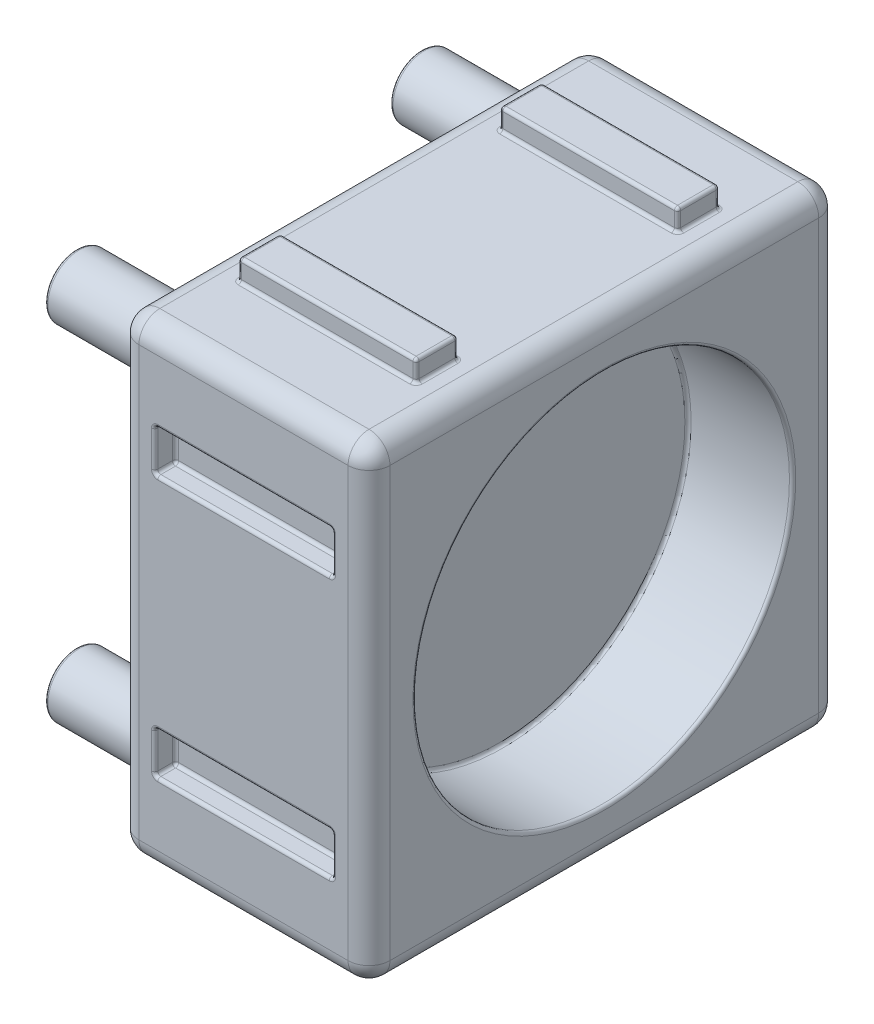
SolidWorks part; units mm, degrees
ref_plane "Front Plane" through (0, 0, 0) normal (0, 0, 1) x (1, 0, 0)
ref_plane "Top Plane" through (0, 0, 0) normal (0, 1, 0) x (1, 0, 0)
ref_plane "Right Plane" through (0, 0, 0) normal (1, 0, 0) x (0, 0, -1)
sketch "Sketch1" plane through (0, 0, 0) normal (0, 1, 0) x (1, 0, 0)
  line L1 (-6, 11.25) -> (6, 11.25)
  line L2 (-6, 11.25) -> (-6, -11.25)
  line L3 (-6, -11.25) -> (6, -11.25)
  line L4 (6, 11.25) -> (6, -11.25)
  line L5 (-6, 11.25) -> (6, -11.25) construction
  line L6 (-6, -11.25) -> (6, 11.25) construction
  point P0 (0, 0)
  dimension "D1" = 22.5
  dimension "D2" = 12
extrude "Boss-Extrude1" add sketch "Sketch1" along normal blind 22.5
sketch "Sketch2" plane through (6, 0, 0) normal (1, 0, 0) x (0, 0, -1)
  line L0 (0, 22.5) -> (0, 0) construction
  line L1 (-11.25, 22.5) -> (11.25, 22.5) construction
  line L2 (-11.25, 0) -> (11.25, 0) construction
  line L3 (-11.25, 11.25) -> (11.25, 11.25) construction
  line L4 (-11.25, 22.5) -> (-11.25, 0) construction
  line L5 (11.25, 22.5) -> (11.25, 0) construction
  circle A0 centre (0, 11.25) radius 9
  dimension "D1" = 18
extrude "Cut-Extrude1" cut sketch "Sketch2" against normal blind 5
sketch "Sketch3" plane through (-6, 0, 0) normal (-1, 0, 0) x (0, 0, 1)
  line L0 (-11.25, 22.5) -> (11.25, 22.5) construction
  line L1 (11.25, 22.5) -> (11.25, 0) construction
  line L2 (0, 0) -> (0, 22.5) construction
  line L3 (-11.25, 0) -> (11.25, 0) construction
  line L4 (11.25, 11.25) -> (-11.25, 11.25) construction
  line L5 (-11.25, 22.5) -> (-11.25, 0) construction
  circle A0 centre (8.25, 19.5) radius 1.5
  circle A1 centre (8.25, 3) radius 1.5
  circle A2 centre (-8.25, 19.5) radius 1.5
  circle A3 centre (-8.25, 3) radius 1.5
  dimension "D1" = 3
  dimension "D2" = 3
  dimension "D3" = 3
extrude "Boss-Extrude2" add sketch "Sketch3" along normal blind 5
sketch "Sketch4" plane through (-6, 0, 0) normal (-1, 0, 0) x (0, 0, 1)
  line L0 (11.25, 11.25) -> (-11.25, 11.25) construction
  line L1 (11.25, 22.5) -> (11.25, 0) construction
  line L2 (-11.25, 22.5) -> (-11.25, 0) construction
  line L3 (0, 0) -> (0, 22.5) construction
  line L4 (-11.25, 0) -> (11.25, 0) construction
  line L5 (-11.25, 22.5) -> (11.25, 22.5) construction
  circle A0 centre (0, 11.25) radius 1.5
  dimension "D1" = 3
extrude "Boss-Extrude3" add sketch "Sketch4" along normal blind 3
fillet "Fillet3" radius 1 12 edges at (-6, 11.25, -11.25) (0, 22.5, -11.25) (0, 0, -11.25) (-6, 0, 0) (0, 22.5, 11.25) (-6, 22.5, 0) (-6, 11.25, 11.25) (0, 0, 11.25) (6, 11.25, 11.25) (6, 0, 0) (6, 11.25, -11.25) (6, 22.5, 0)
sketch "Sketch5" plane through (0, 0, 0) normal (0, -1, 0) x (-1, 0, 0)
  line L0 (5, 10.25) -> (-5, 10.25) construction
  line L1 (4.25, 7.25) -> (-4.25, 7.25)
  line L2 (4.25, 7.25) -> (4.25, 5.25)
  line L3 (4.25, 5.25) -> (-4.25, 5.25)
  line L4 (-4.25, 7.25) -> (-4.25, 5.25)
  line L5 (-6, -10.25) -> (-6, 10.25) construction
  line L7 (-6, 0) -> (5, 0) construction
  line L8 (5, -10.25) -> (5, 10.25) construction
  line L9 (4.25, -7.25) -> (4.25, -5.25)
  line L10 (-4.25, -7.25) -> (-4.25, -5.25)
  line L11 (4.25, -7.25) -> (-4.25, -7.25)
  line L12 (4.25, -5.25) -> (-4.25, -5.25)
  dimension "D1" = 3
  dimension "D2" = 0.75
  dimension "D3" = 2
  dimension "D4" = 8.5
extrude "Cut-Extrude2" cut sketch "Sketch5" against normal blind 1
sketch "Sketch6" plane through (0, 0, 11.25) normal (0, 0, 1) x (1, 0, 0)
  line L0 (-5, 1) -> (5, 1) construction
  line L1 (-4.25, 4) -> (4.25, 4)
  line L2 (-4.25, 4) -> (-4.25, 6)
  line L3 (-4.25, 6) -> (4.25, 6)
  line L4 (4.25, 4) -> (4.25, 6)
  line L5 (5, 1) -> (5, 21.5) construction
  line L6 (5, 11.25) -> (-5, 11.25) construction
  line L7 (-5, 21.5) -> (-5, 1) construction
  line L8 (-4.25, 18.5) -> (-4.25, 16.5)
  line L9 (4.25, 18.5) -> (4.25, 16.5)
  line L10 (-4.25, 18.5) -> (4.25, 18.5)
  line L11 (-4.25, 16.5) -> (4.25, 16.5)
  dimension "D1" = 3
  dimension "D2" = 0.75
  dimension "D3" = 8.5
  dimension "D4" = 2
extrude "Cut-Extrude3" cut sketch "Sketch6" against normal blind 1
sketch "Sketch7" plane through (0, 22.5, 0) normal (0, 1, 0) x (1, 0, 0)
  line L0 (-5, -10.25) -> (5, -10.25) construction
  line L1 (-4.25, -7.25) -> (4.25, -7.25)
  line L2 (-4.25, -7.25) -> (-4.25, -5.25)
  line L3 (-4.25, -5.25) -> (4.25, -5.25)
  line L4 (4.25, -7.25) -> (4.25, -5.25)
  line L5 (5, -10.25) -> (5, 10.25) construction
  line L6 (-5, 0) -> (5, 0) construction
  line L7 (-5, 10.25) -> (-5, -10.25) construction
  line L8 (4.25, 7.25) -> (4.25, 5.25)
  line L9 (-4.25, 7.25) -> (-4.25, 5.25)
  line L10 (-4.25, 7.25) -> (4.25, 7.25)
  line L11 (-4.25, 5.25) -> (4.25, 5.25)
  dimension "D1" = 3
  dimension "D2" = 0.75
  dimension "D3" = 8.5
  dimension "D4" = 2
extrude "Boss-Extrude4" add sketch "Sketch7" along normal blind 1
sketch "Sketch8" plane through (0, 0, -11.25) normal (0, 0, -1) x (-1, 0, 0)
  line L0 (5, 21.5) -> (-5, 21.5) construction
  line L1 (4.25, 18.5) -> (-4.25, 18.5)
  line L2 (4.25, 18.5) -> (4.25, 16.5)
  line L3 (4.25, 16.5) -> (-4.25, 16.5)
  line L4 (-4.25, 18.5) -> (-4.25, 16.5)
  line L5 (-5, 21.5) -> (-5, 1) construction
  line L6 (5, 11.25) -> (-5, 11.25) construction
  line L7 (5, 1) -> (5, 21.5) construction
  line L8 (-4.25, 4) -> (-4.25, 6)
  line L9 (4.25, 4) -> (-4.25, 4)
  line L10 (4.25, 4) -> (4.25, 6)
  line L11 (4.25, 6) -> (-4.25, 6)
  dimension "D1" = 3
  dimension "D2" = 0.75
  dimension "D3" = 8.5
  dimension "D4" = 2
extrude "Boss-Extrude5" add sketch "Sketch8" along normal blind 1
fillet "Fillet4" radius 0.15 96 edges at (-4.25, 17.5, 10.25) (-4.25, 17.5, 11.25) (0, 18.5, 10.25) (-4.25, 18.5, 10.75) (0, 18.5, 11.25) (4.25, 17.5, 10.25) (4.25, 18.5, 10.75) (4.25, 17.5, 11.25) (-4.25, 16.5, 10.75) (0, 16.5, 10.25) (4.25, 16.5, 10.75) (0, 16.5, 11.25) (0, 4, 10.25) (0, 4, 11.25) (4.25, 4, 10.75) (4.25, 5, 10.25) (4.25, 5, 11.25) (4.25, 6, 10.75) (0, 6, 10.25) (0, 6, 11.25) (-4.25, 6, 10.75) (-4.25, 5, 10.25) (-4.25, 4, 10.75) (-4.25, 5, 11.25) (4.25, 1, 6.25) (4.25, 0, 6.25) (4.25, 0.5, 7.25) (0, 1, 7.25) (0, 0, 7.25) (0, 1, 5.25) (4.25, 0.5, 5.25) (0, 0, 5.25) (-4.25, 0.5, 7.25) (-4.25, 1, 6.25) (-4.25, 0.5, 5.25) (-4.25, 0, 6.25) (-4.25, 1, -6.25) (-4.25, 0, -6.25) (-4.25, 0.5, -7.25) (0, 1, -7.25) (0, 0, -7.25) (4.25, 0.5, -7.25) (4.25, 1, -6.25) (4.25, 0, -6.25) (4.25, 0.5, -5.25) (0, 1, -5.25) (-4.25, 0.5, -5.25) (0, 0, -5.25) (-4.25, 5, -12.25) (-4.25, 5, -11.25) (-4.25, 6, -11.75) (0, 6, -12.25) (0, 6, -11.25) (0, 4, -12.25) (-4.25, 4, -11.75) (0, 4, -11.25) (4.25, 6, -11.75) (4.25, 5, -12.25) (4.25, 4, -11.75) (4.25, 5, -11.25) (4.25, 17.5, -12.25) (4.25, 17.5, -11.25) (4.25, 16.5, -11.75) (0, 16.5, -12.25) (0, 16.5, -11.25) (-4.25, 16.5, -11.75) (-4.25, 17.5, -12.25) (-4.25, 17.5, -11.25) (-4.25, 18.5, -11.75) (0, 18.5, -12.25) (4.25, 18.5, -11.75) (0, 18.5, -11.25) (-4.25, 23.5, -6.25) (-4.25, 22.5, -6.25) (-4.25, 23, -5.25) (0, 23.5, -5.25) (0, 22.5, -5.25) (0, 23.5, -7.25) (-4.25, 23, -7.25) (0, 22.5, -7.25) (4.25, 23, -5.25) (4.25, 23.5, -6.25) (4.25, 23, -7.25) (4.25, 22.5, -6.25) (0, 23.5, 5.25) (0, 22.5, 5.25) (4.25, 23.5, 6.25) (4.25, 23, 5.25) (4.25, 22.5, 6.25) (0, 23.5, 7.25) (4.25, 23, 7.25) (0, 22.5, 7.25) (-4.25, 23, 5.25) (-4.25, 23.5, 6.25) (-4.25, 23, 7.25) (-4.25, 22.5, 6.25)
fillet "Fillet5" radius 0.15 10 edges at (-6, 3, 6.75) (-11, 3, 6.75) (-6, 19.5, 6.75) (-11, 19.5, 9.75) (-6, 19.5, -9.75) (-11, 19.5, -9.75) (-6, 11.25, -1.5) (-9, 11.25, 1.5) (-6, 3, -9.75) (-11, 3, -6.75)
fillet "Fillet6" radius 0.15 2 edges at (6, 11.25, -9) (1, 11.25, -9)
